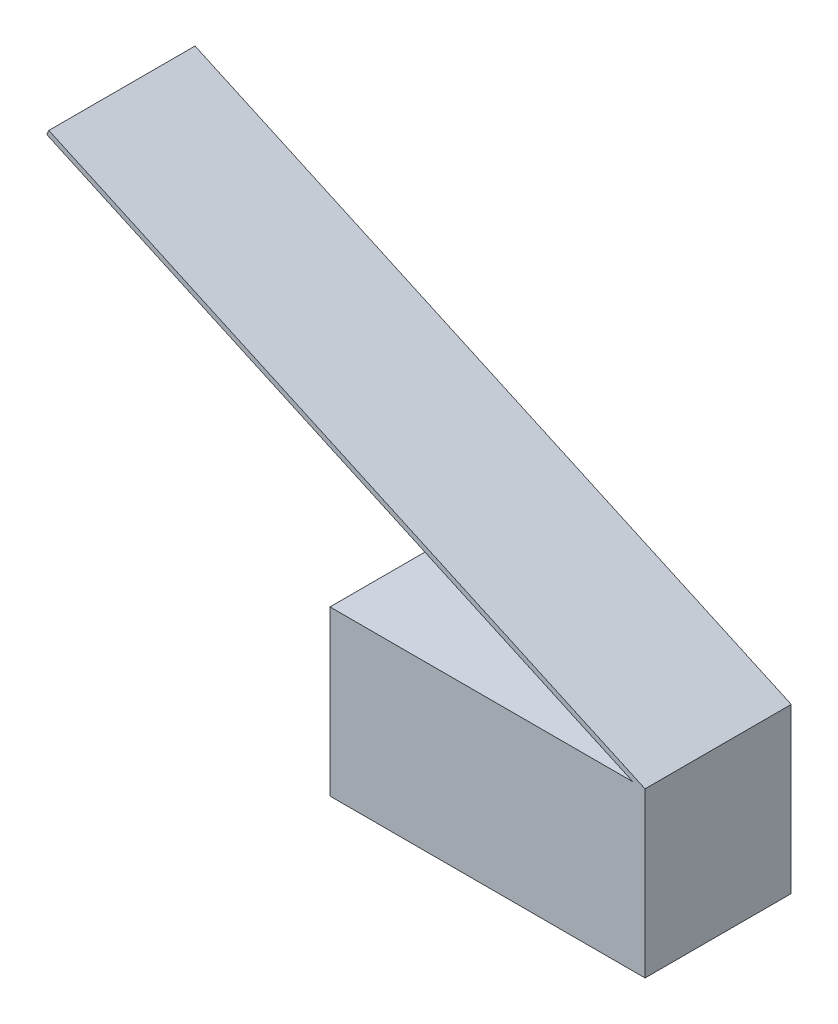
SolidWorks part; units mm, degrees
ref_plane "前视基准面" through (0, 0, 0) normal (0, 0, 1) x (1, 0, 0)
ref_plane "上视基准面" through (0, 0, 0) normal (0, 1, 0) x (1, 0, 0)
ref_plane "右视基准面" through (0, 0, 0) normal (1, 0, 0) x (0, 0, -1)
sketch "草图1" plane through (0, 0, 0) normal (0, 1, 0) x (1, 0, 0)
  line L1 (-6.4672, 2.8234) -> (6.0328, 2.8234)
  line L2 (-6.4672, 2.8234) -> (-6.4672, -2.9766)
  line L3 (-6.4672, -2.9766) -> (6.0328, -2.9766)
  line L4 (6.0328, 2.8234) -> (6.0328, -2.9766)
  line L5 (-6.4672, 2.8234) -> (6.0328, -2.9766) construction
  line L6 (-6.4672, -2.9766) -> (6.0328, 2.8234) construction
  point P4 (-0.2172, -0.0766)
  dimension "D1" = 12.5
  dimension "D2" = 5.8
extrude "凸台-拉伸1" add sketch "草图1" along normal blind 6.5
sketch "草图2" plane through (0, 0, 2.9766) normal (0, 0, 1) x (1, 0, 0)
  line L0 (6.0328, 6.5) -> (-17.6204, 17.2948)
  line L1 (-17.6204, 17.2948) -> (-17.7034, 17.1128)
  line L2 (-17.7034, 17.1128) -> (5.5511, 6.5)
  line L3 (-6.4672, 6.5) -> (6.0328, 6.5) construction
  line L4 (5.5511, 6.5) -> (6.0328, 6.5)
  dimension "D1" = 26
  dimension "D2" = 0.2
extrude "凸台-拉伸2" add sketch "草图2" against normal through all
